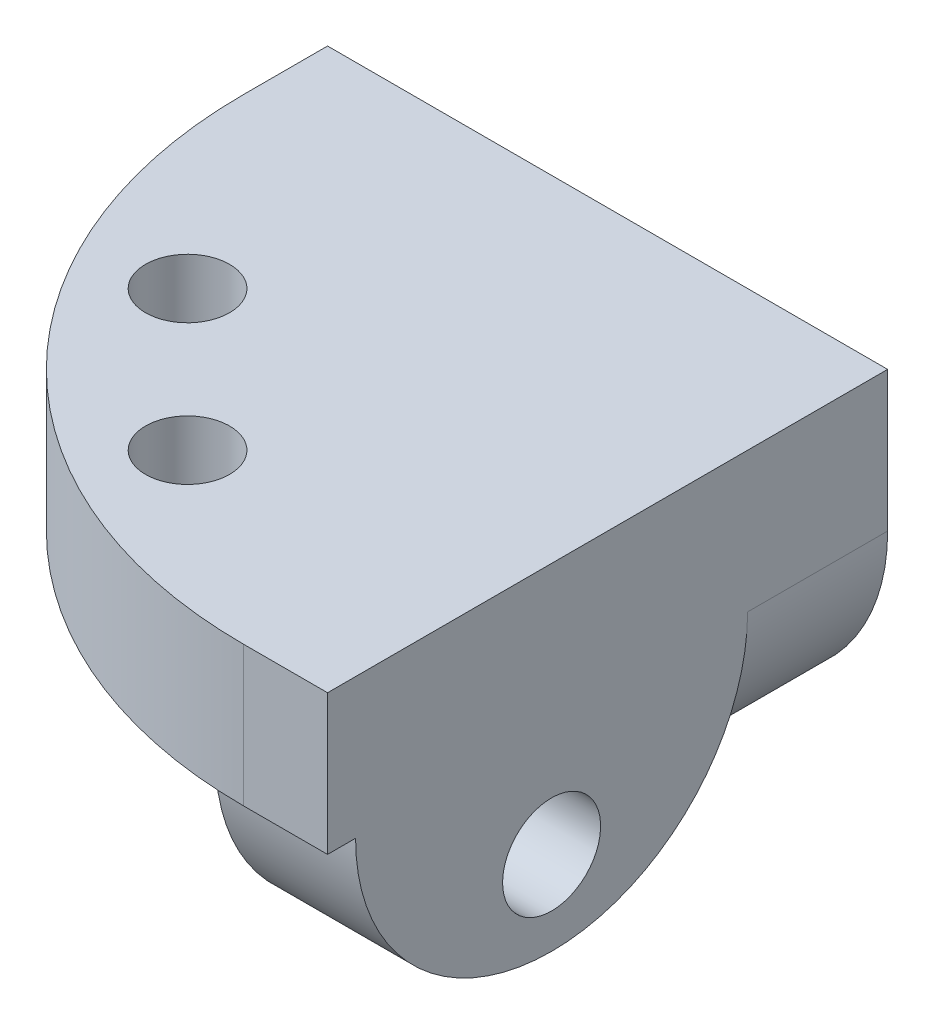
SolidWorks part; units mm, degrees
ref_plane "Front Plane" through (0, 0, 0) normal (0, 0, 1) x (1, 0, 0)
ref_plane "Top Plane" through (0, 0, 0) normal (0, 1, 0) x (1, 0, 0)
ref_plane "Right Plane" through (0, 0, 0) normal (1, 0, 0) x (0, 0, -1)
sketch "Sketch1" plane through (0, 0, 0) normal (0, 1, 0) x (1, 0, 0)
  line L0 (0, 15) -> (20, 15) construction
  line L1 (0, 0) -> (20, 0)
  line L2 (0, 0) -> (0, 20)
  line L3 (0, 20) -> (20, 20)
  line L4 (20, 0) -> (20, 20)
  line L5 (15, 20) -> (15, 0) construction
  line L6 (0, 15) -> (10, 15) construction
  line L7 (15, 0) -> (15, 10) construction
  circle A0 centre (10, 15) radius 1.5
  circle A1 centre (15, 10) radius 1.5
  dimension "D1" = 20
  dimension "D2" = 15
  dimension "D3" = 15
extrude "Boss-Extrude1" add sketch "Sketch1" along normal blind 5
sketch "Sketch2" plane through (0, 0, 0) normal (0, 0, 1) x (1, 0, 0)
  line L0 (0, 0) -> (20, 0) construction
  line L1 (19, 0) -> (5, 0)
  line L2 (12, 0) -> (12, -7) construction
  arc A0 (5, 0) -> (19, 0) centre (12, 0) ccw
  circle A1 centre (12, -4) radius 1.75
  dimension "D1" = 5
  dimension "D3" = 4
  dimension "D2" = 14
extrude "Boss-Extrude2" add sketch "Sketch2" against normal blind 5
sketch "Sketch3" plane through (0, 0, 0) normal (-1, 0, 0) x (0, 0, 1)
  line L0 (-20, 0) -> (0, 0) construction
  line L1 (0, 0) -> (-14, 0)
  line L2 (-7, 0) -> (-7, -7) construction
  arc A0 (0, 0) -> (-14, 0) centre (-7, 0) cw
  circle A1 centre (-7, -4) radius 1.75
  dimension "D1" = 0
  dimension "D3" = 4
  dimension "D4" = 3.5
  dimension "D2" = 14
extrude "Boss-Extrude3" add sketch "Sketch3" against normal blind 5
fillet "Fillet1" radius 17 1 edges at (20, 2.5, -20)
sketch "Sketch4" plane through (0, 0, 0) normal (0, -1, 0) x (1, 0, 0)
  line L0 (0, 0) -> (0, -36.9038) construction
  line L1 (0, -36.9038) -> (36.9038, 0) construction
  line L2 (0, 0) -> (36.9038, 0) construction
  dimension "D1" = 45
ref_plane "Plane1" through (18.4519, 0, -18.4519) normal (0.7071, 0, -0.7071) x (0.7071, 0, 0.7071)
mirror "Mirror2" about plane through (18.4519, 0, -18.4519) normal (0.7071, 0, -0.7071) of bodies 103 102
ref_plane "Plane2" through (3, 0, -20) normal (1, 0, 0) x (0, 0, -1)
sketch "Sketch6" plane through (0, 0, 0) normal (-1, 0, 0) x (0, 0, 1)
  line L4 (0, 5) -> (-20.0029, 5)
  line L5 (0, 5) -> (0, -9.0576)
  line L14 (0, -9.0576) -> (-20.0029, -9.0576)
  line L15 (-20.0029, 5) -> (-20.0029, -9.0576)
  dimension "D1" = 14.0576
  dimension "D2" = 20.0029
extrude "Cut-Extrude1" cut sketch "Sketch6" against normal blind 21
